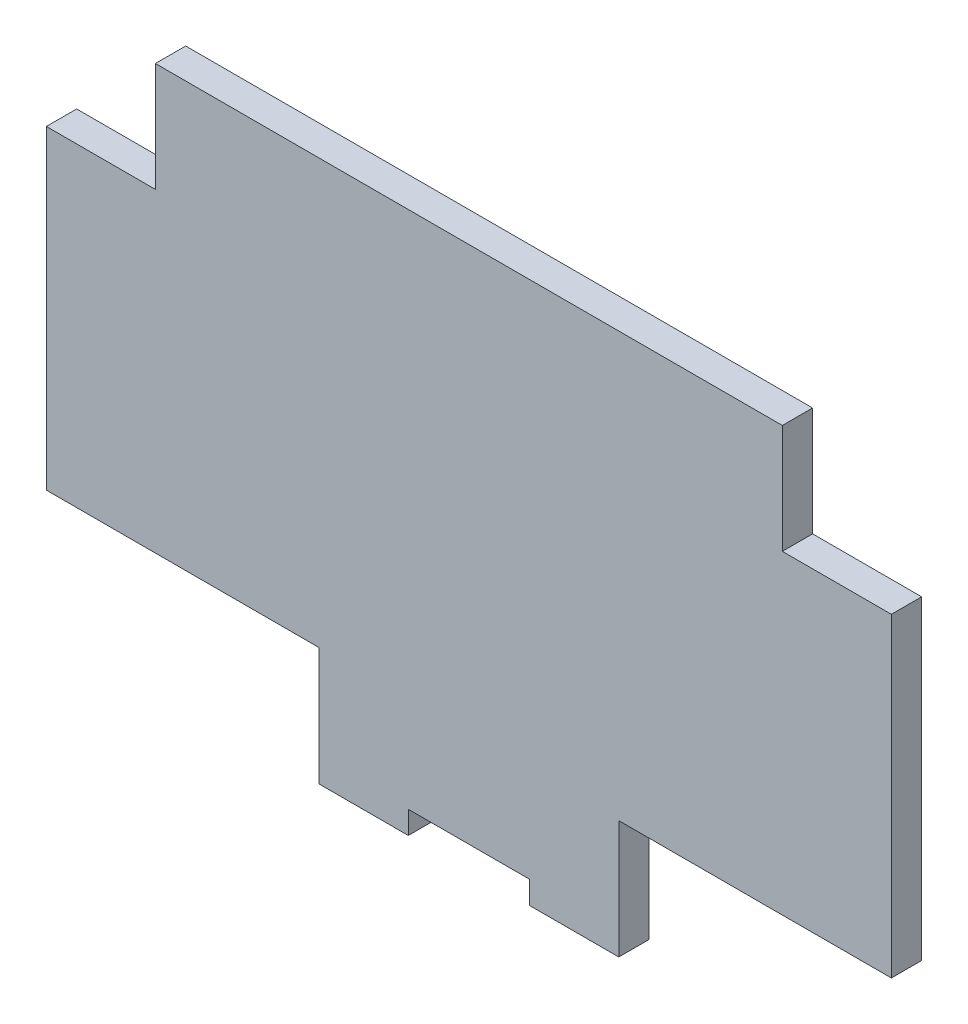
SolidWorks part; units mm, degrees
ref_plane "Front Plane" through (0, 0, 0) normal (0, 0, 1) x (1, 0, 0)
ref_plane "Top Plane" through (0, 0, 0) normal (0, 1, 0) x (1, 0, 0)
ref_plane "Right Plane" through (0, 0, 0) normal (1, 0, 0) x (0, 0, -1)
sketch "Sketch1" plane through (0, 0, 0) normal (0, 0, 1) x (1, 0, 0)
  line L19 (-4, -19.4) -> (4, -19.4)
  line L20 (-4, -19.4) -> (-4, -16.4)
  line L21 (-4, -16.4) -> (4, -16.4)
  line L22 (4, -19.4) -> (4, -16.4)
  line L23 (-4, -19.4) -> (4, -16.4) construction
  line L24 (-4, -16.4) -> (4, -19.4) construction
  line L42 (-9.9, -17.9) -> (9.9, -17.9)
  line L43 (-9.9, -10.1) -> (-9.9, -17.9)
  line L44 (-27.9, -10.1) -> (-9.9, -10.1)
  line L45 (-27.9, 10.7) -> (-27.9, -10.1)
  line L46 (-20.7, 10.7) -> (-27.9, 10.7)
  line L47 (-20.7, 17.9) -> (-20.7, 10.7)
  line L48 (20.7, 17.9) -> (-20.7, 17.9)
  line L49 (20.7, 10.7) -> (20.7, 17.9)
  line L50 (27.9, 10.7) -> (20.7, 10.7)
  line L51 (27.9, -10.1) -> (27.9, 10.7)
  line L52 (9.9, -10.1) -> (27.9, -10.1)
  line L53 (9.9, -17.9) -> (9.9, -10.1)
  line L54 (-9.9, -17.9) -> (9.9, -17.9)
  line L55 (-9.9, -10.1) -> (-9.9, -17.9)
  line L56 (-27.9, -10.1) -> (-9.9, -10.1)
  line L57 (-27.9, 10.7) -> (-27.9, -10.1)
  line L58 (-20.7, 10.7) -> (-27.9, 10.7)
  line L59 (-20.7, 17.9) -> (-20.7, 10.7)
  line L60 (20.7, 17.9) -> (-20.7, 17.9)
  line L61 (20.7, 10.7) -> (20.7, 17.9)
  line L62 (27.9, 10.7) -> (20.7, 10.7)
  line L63 (27.9, -10.1) -> (27.9, 10.7)
  line L64 (9.9, -10.1) -> (27.9, -10.1)
  line L65 (9.9, -17.9) -> (9.9, -10.1)
  point P0 (0, -17.9)
  dimension "D2" = 8
  dimension "D3" = 1.5
  dimension "D1" = 0.1
extrude "Boss-Extrude1" add sketch "Sketch1" against normal blind 2 contours L54 L65 L64 L63 L62 L61 L60 L59 L58 L57 L56 L55 L20 L21 L22
sketch "Sketch2" plane through (0, 0, -2) normal (0, 0, -1) x (-1, 0, 0)
  line L0 (0, 17.9) -> (0, -16.4) construction
  line L1 (-20.7, 17.9) -> (20.7, 17.9) construction
  line L2 (4, -16.4) -> (-4, -16.4) construction
  line L4 (-20, -8.2) -> (20, -8.2)
  line L5 (-20, -8.2) -> (-20, 4.8)
  line L6 (-20, 4.8) -> (20, 4.8)
  line L7 (20, -8.2) -> (20, 4.8)
  line L8 (-20, -8.2) -> (20, 4.8) construction
  line L9 (-20, 4.8) -> (20, -8.2) construction
  point P6 (0, -1.7)
  dimension "D1" = 13
  dimension "D2" = 40
extrude "Boss-Extrude2" add sketch "Sketch2" along normal blind 2.8
